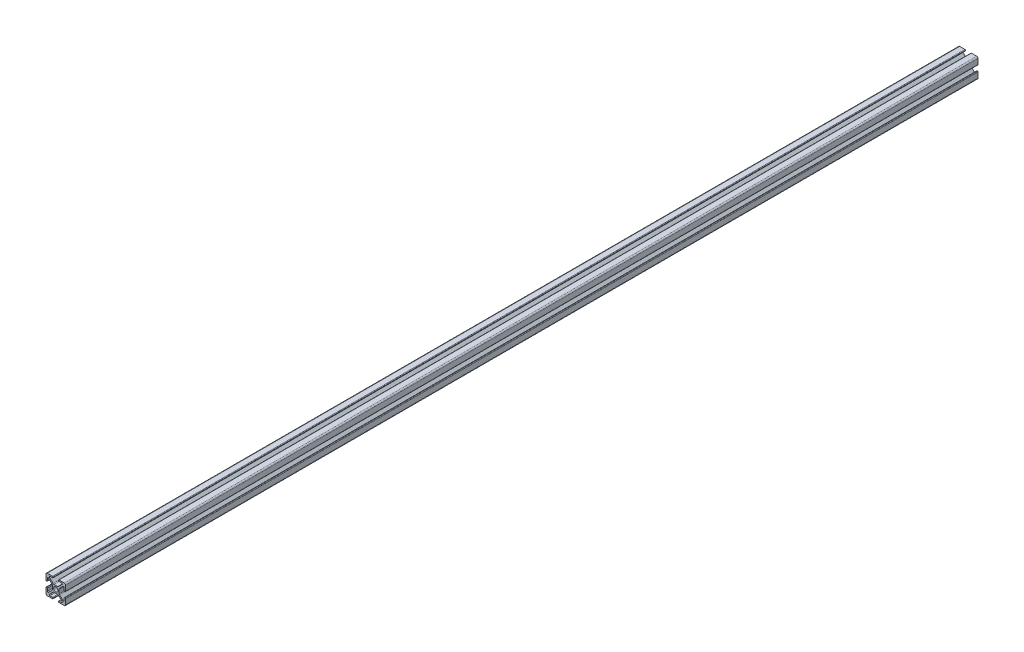
SolidWorks part; units mm, degrees
ref_plane "前视基准面" through (0, 0, 0) normal (0, 0, 1) x (1, 0, 0)
ref_plane "上视基准面" through (0, 0, 0) normal (0, 1, 0) x (1, 0, 0)
ref_plane "右视基准面" through (0, 0, 0) normal (1, 0, 0) x (0, 0, -1)
sketch "草图1" plane through (0, 0, 0) normal (0, 0, 1) x (1, 0, 0)
  line L0 (14.1, -4) -> (13.9, -4)
  line L1 (11.2929, -9.6929) -> (5.8358, -4.2358)
  line L2 (5.25, -2.8216) -> (5.25, 2.8216)
  line L3 (5.8358, 4.2358) -> (11.2929, 9.6929)
  line L4 (9.6929, 11.2929) -> (4.2358, 5.8358)
  line L5 (2.8216, 5.25) -> (-2.8216, 5.25)
  line L6 (-4.2358, 5.8358) -> (-9.6929, 11.2929)
  line L7 (-11.2929, 9.6929) -> (-5.8358, 4.2358)
  line L8 (-5.25, 2.8216) -> (-5.25, -2.8216)
  line L9 (-5.8358, -4.2358) -> (-11.2929, -9.6929)
  line L10 (-9.6929, -11.2929) -> (-4.2358, -5.8358)
  line L11 (-2.8216, -5.25) -> (2.8216, -5.25)
  line L12 (4.2358, -5.8358) -> (9.6929, -11.2929)
  line L13 (8.9858, -13) -> (4.9, -13)
  line L14 (4, -13.9) -> (4, -14.1)
  line L15 (15, -4.9) -> (15, -13)
  line L16 (4.9, -15) -> (13, -15)
  line L17 (13, -8.9858) -> (13, -4.9)
  line L18 (14.1, 4) -> (13.9, 4)
  line L19 (8.9858, 13) -> (4.9, 13)
  line L20 (4, 13.9) -> (4, 14.1)
  line L21 (4.9, 15) -> (13, 15)
  line L22 (15, 4.9) -> (15, 13)
  line L23 (13, 8.9858) -> (13, 4.9)
  line L24 (-14.1, -4) -> (-13.9, -4)
  line L25 (-8.9858, -13) -> (-4.9, -13)
  line L26 (-4, -13.9) -> (-4, -14.1)
  line L27 (-4.9, -15) -> (-13, -15)
  line L28 (-15, -4.9) -> (-15, -13)
  line L29 (-13, -8.9858) -> (-13, -4.9)
  line L30 (-14.1, 4) -> (-13.9, 4)
  line L31 (-8.9858, 13) -> (-4.9, 13)
  line L32 (-4, 13.9) -> (-4, 14.1)
  line L33 (-4.9, 15) -> (-13, 15)
  line L34 (-15, 4.9) -> (-15, 13)
  line L35 (-13, 8.9858) -> (-13, 4.9)
  circle A0 centre (0, 0) radius 3.35
  arc A1 (11.2929, -9.6929) -> (13, -8.9858) centre (12, -8.9858) ccw
  arc A2 (5.25, -2.8216) -> (5.8358, -4.2358) centre (7.25, -2.8216) ccw
  arc A3 (5.8358, 4.2358) -> (5.25, 2.8216) centre (7.25, 2.8216) ccw
  arc A4 (13, 8.9858) -> (11.2929, 9.6929) centre (12, 8.9858) ccw
  arc A5 (9.6929, 11.2929) -> (8.9858, 13) centre (8.9858, 12) ccw
  arc A6 (2.8216, 5.25) -> (4.2358, 5.8358) centre (2.8216, 7.25) ccw
  arc A7 (-4.2358, 5.8358) -> (-2.8216, 5.25) centre (-2.8216, 7.25) ccw
  arc A8 (-8.9858, 13) -> (-9.6929, 11.2929) centre (-8.9858, 12) ccw
  arc A9 (-11.2929, 9.6929) -> (-13, 8.9858) centre (-12, 8.9858) ccw
  arc A10 (-5.25, 2.8216) -> (-5.8358, 4.2358) centre (-7.25, 2.8216) ccw
  arc A11 (-5.8358, -4.2358) -> (-5.25, -2.8216) centre (-7.25, -2.8216) ccw
  arc A12 (-13, -8.9858) -> (-11.2929, -9.6929) centre (-12, -8.9858) ccw
  arc A13 (-9.6929, -11.2929) -> (-8.9858, -13) centre (-8.9858, -12) ccw
  arc A14 (-2.8216, -5.25) -> (-4.2358, -5.8358) centre (-2.8216, -7.25) ccw
  arc A15 (4.2358, -5.8358) -> (2.8216, -5.25) centre (2.8216, -7.25) ccw
  arc A16 (8.9858, -13) -> (9.6929, -11.2929) centre (8.9858, -12) ccw
  arc A17 (13.9, -4) -> (13, -4.9) centre (13.9, -4.9) ccw
  arc A18 (15, -4.9) -> (14.1, -4) centre (14.1, -4.9) ccw
  arc A19 (4.9, -13) -> (4, -13.9) centre (4.9, -13.9) ccw
  arc A20 (4, -14.1) -> (4.9, -15) centre (4.9, -14.1) ccw
  arc A21 (13, -15) -> (15, -13) centre (13, -13) ccw
  arc A22 (13, 4.9) -> (13.9, 4) centre (13.9, 4.9) ccw
  arc A23 (4, 13.9) -> (4.9, 13) centre (4.9, 13.9) ccw
  arc A24 (4.9, 15) -> (4, 14.1) centre (4.9, 14.1) ccw
  arc A25 (15, 13) -> (13, 15) centre (13, 13) ccw
  arc A26 (14.1, 4) -> (15, 4.9) centre (14.1, 4.9) ccw
  arc A27 (-13, -4.9) -> (-13.9, -4) centre (-13.9, -4.9) ccw
  arc A28 (-4, -13.9) -> (-4.9, -13) centre (-4.9, -13.9) ccw
  arc A29 (-4.9, -15) -> (-4, -14.1) centre (-4.9, -14.1) ccw
  arc A30 (-15, -13) -> (-13, -15) centre (-13, -13) ccw
  arc A31 (-14.1, -4) -> (-15, -4.9) centre (-14.1, -4.9) ccw
  arc A32 (-13.9, 4) -> (-13, 4.9) centre (-13.9, 4.9) ccw
  arc A33 (-4.9, 13) -> (-4, 13.9) centre (-4.9, 13.9) ccw
  arc A34 (-4, 14.1) -> (-4.9, 15) centre (-4.9, 14.1) ccw
  arc A35 (-13, 15) -> (-15, 13) centre (-13, 13) ccw
  arc A36 (-15, 4.9) -> (-14.1, 4) centre (-14.1, 4.9) ccw
  point P0 (0, 0.001)
  point P1 (0.001, 0.001)
  point P2 (0.001, 0)
extrude "凸台-拉伸1" add sketch "草图1" along normal blind 1400
sketch "Sketch1" plane through (5.25, 0, 0) normal (1, 0, 0) x (0, 0, -1)
  line L0 (0, 0) -> (-2206.6738, 0) construction
  line L1 (-1040.5, 103.8298) -> (-1040.5, -185.7534) construction
  circle A0 centre (-1040.5, 0) radius 3
  circle A1 centre (-15, 0) radius 3
  circle A2 centre (-2066, 0) radius 3
  dimension "D2" = 15
  dimension "D3" = 6
  dimension "D4" = 6
  dimension "D1" = 1040.5
extrude "Cut-Extrude1" [suppressed] cut sketch "Sketch1" against normal blind 300
